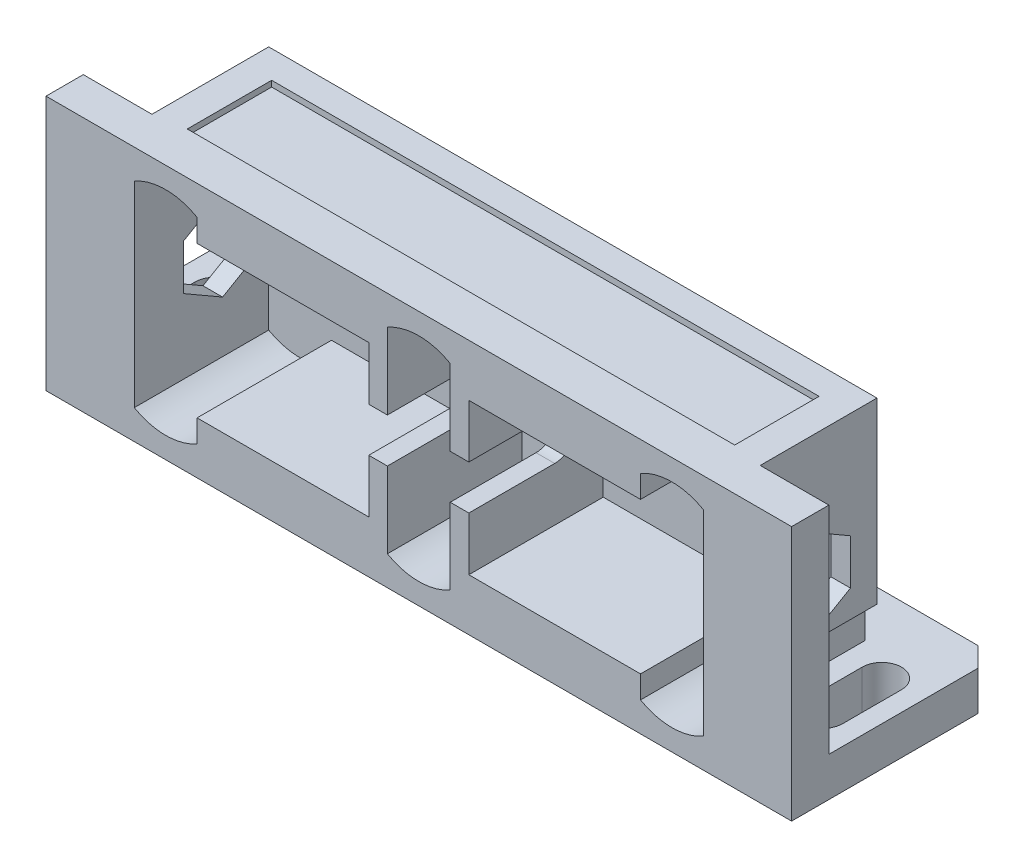
SolidWorks part; units mm, degrees
ref_plane "Front Plane" through (0, 0, 0) normal (0, 0, 1) x (1, 0, 0)
ref_plane "Top Plane" through (0, 0, 0) normal (0, 1, 0) x (1, 0, 0)
ref_plane "Right Plane" through (0, 0, 0) normal (1, 0, 0) x (0, 0, -1)
sketch "Sketch1" plane through (0, 0, 0) normal (0, 1, 0) x (1, 0, 0)
  line L1 (38, 10.5) -> (-38, 10.5)
  line L2 (38, 10.5) -> (38, -10.5)
  line L3 (38, -10.5) -> (-38, -10.5)
  line L4 (-38, 10.5) -> (-38, -10.5)
  line L5 (38, 10.5) -> (-38, -10.5) construction
  line L6 (38, -10.5) -> (-38, 10.5) construction
  point P0 (0, 0)
  dimension "D1" = 76
  dimension "D2" = 21
extrude "Boss-Extrude1" add sketch "Sketch1" along normal blind 4
sketch "Sketch2" plane through (0, 0, 0) normal (0, 1, 0) x (1, 0, 0)
  line L0 (-38, 10.5) -> (-38, -10.5) construction
  line L1 (-38, -6.7) -> (38, -6.7)
  line L2 (-38, -6.7) -> (-38, -10.5)
  line L3 (-38, -10.5) -> (38, -10.5)
  line L4 (38, -6.7) -> (38, -10.5)
  dimension "D1" = 3.8
extrude "Boss-Extrude2" add sketch "Sketch2" along normal blind 26
sketch "Sketch3" plane through (0, 0, 10.5) normal (0, 0, -1) x (-1, 0, 0)
  line L0 (-38, 26) -> (38, 26) construction
  line L1 (-31, 26) -> (31, 26)
  line L2 (-31, 26) -> (-31, 4)
  line L3 (-31, 4) -> (31, 4)
  line L4 (31, 26) -> (31, 4)
  line L5 (-38, 4) -> (38, 4) construction
  line L6 (0, 4) -> (0, 0) construction
  line L7 (-38, 0) -> (38, 0) construction
  dimension "D1" = 62
extrude "Boss-Extrude3" add sketch "Sketch3" along normal blind 15.7
chamfer "Chamfer2" distance 2 angle 45 2 edges at (-38, 2, -10.5) (38, 2, -10.5)
sketch "Sketch4" plane through (0, 26, 0) normal (0, 1, 0) x (1, 0, 0)
  line L3 (31, 5.2) -> (-31, 5.2) construction
  line L4 (-27.9, 2.4) -> (27.9, 2.4)
  line L5 (-27.9, 2.4) -> (-27.9, -6.2)
  line L6 (-27.9, -6.2) -> (27.9, -6.2)
  line L7 (27.9, 2.4) -> (27.9, -6.2)
  line L8 (31, 5.2) -> (31, -6.7) construction
  line L9 (0, 0) -> (0, -6.2) construction
  line L10 (-38, -10.5) -> (38, -10.5) construction
  dimension "D1" = 2.8
  dimension "D2" = 3.1
  dimension "D3" = 4.3
extrude "Cut-Extrude1" cut sketch "Sketch4" against normal blind 0.6
sketch "Sketch5" plane through (0, 4, 0) normal (0, 1, 0) x (1, 0, 0)
  line L0 (-34, 2.7) -> (-34, -3.3) construction
  line L1 (-32, 2.7) -> (-32, -3.3)
  line L2 (-36, 2.7) -> (-36, -3.3)
  line L3 (0, 0) -> (0, 10.5) construction
  line L4 (36, 10.5) -> (-36, 10.5) construction
  line L5 (34, 2.7) -> (34, -3.3) construction
  line L6 (32, 2.7) -> (32, -3.3)
  line L7 (36, 2.7) -> (36, -3.3)
  line L8 (-38, 8.5) -> (-38, -6.7) construction
  arc A0 (-32, 2.7) -> (-36, 2.7) centre (-34, 2.7) ccw
  arc A1 (-36, -3.3) -> (-32, -3.3) centre (-34, -3.3) ccw
  arc A2 (32, 2.7) -> (36, 2.7) centre (34, 2.7) cw
  arc A3 (36, -3.3) -> (32, -3.3) centre (34, -3.3) cw
  point P2 (-34, -0.3)
  point P14 (34, -0.3)
  point P19 (-34, 4.7)
  dimension "D1" = 4
  dimension "D2" = 8
  dimension "D3" = 5.8
  dimension "D4" = 2
extrude "Cut-Extrude2" cut sketch "Sketch5" against normal through all
sketch "Sketch6" plane through (0, 0, -10.5) normal (0, 0, -1) x (-1, 0, 0)
  line L0 (0, 0) -> (0, 26) construction
  line L1 (-16.75, 1.1) -> (-8.75, 1.1)
  line L2 (-16.75, 1.1) -> (-16.75, 5.1)
  line L3 (-16.75, 5.1) -> (-8.75, 5.1)
  line L4 (-8.75, 1.1) -> (-8.75, 5.1)
  line L5 (31, 26) -> (-31, 26) construction
  line L6 (8.75, 1.1) -> (8.75, 5.1)
  line L7 (16.75, 5.1) -> (8.75, 5.1)
  line L8 (16.75, 1.1) -> (16.75, 5.1)
  line L9 (16.75, 1.1) -> (8.75, 1.1)
  line L10 (-36, 0) -> (36, 0) construction
  dimension "D1" = 8
  dimension "D2" = 4
  dimension "D3" = 1.1
  dimension "D4" = 17.5
extrude "Cut-Extrude3" cut sketch "Sketch6" against normal blind 19.7
sketch "Sketch7" plane through (0, 0, 10.5) normal (0, 0, 1) x (1, 0, 0)
  line L0 (-38, 13) -> (0, 13) construction
  line L1 (29, 5.3) -> (-29, 5.3)
  line L2 (29, 5.3) -> (29, 20.7)
  line L3 (29, 20.7) -> (-29, 20.7)
  line L4 (-29, 5.3) -> (-29, 20.7)
  line L5 (29, 5.3) -> (-29, 20.7) construction
  line L6 (29, 20.7) -> (-29, 5.3) construction
  line L7 (-38, 26) -> (-38, 0) construction
  point P0 (0, 13)
  dimension "D1" = 58
  dimension "D2" = 15.4
extrude "Cut-Extrude4" cut sketch "Sketch7" against normal blind 13.7
sketch "Sketch8" plane through (0, 0, 10.5) normal (0, 0, 1) x (1, 0, 0)
  line L0 (-29, 20.7) -> (-29, 5.3) construction
  line L9 (-29, 20.7) -> (-29, 5.3) construction
  line L10 (-29, 23) -> (-22.6, 23) construction
  line L11 (-38, 13) -> (-29, 13) construction
  line L12 (-29, 23) -> (-29, 3)
  line L13 (-29, 3) -> (-22.6, 3) construction
  line L14 (-22.6, 23) -> (-22.6, 3)
  line L16 (-38, 26) -> (-38, 0) construction
  arc A0 (-29, 23) -> (-22.6, 23) centre (-25.8, 17.4015) cw
  arc A1 (-29, 3) -> (-22.6, 3) centre (-25.8, 8.5985) ccw
  point P9 (-25.8, 23.85)
  point P11 (-25.8, 2.15)
  dimension "D2" = 21.7
  dimension "D1" = 6.4
  dimension "D3" = 20
extrude "Cut-Extrude5" cut sketch "Sketch8" against normal up to surface (13.7 mm away) up to face at (0, 13, -3.2)
pattern_linear "LPattern1" count 3 spacing 25.8 along (1, 0, 0) of "Cut-Extrude5"
sketch "Sketch9" plane through (0, 0, 10.5) normal (0, 0, 1) x (1, 0, 0)
  line L0 (-22.6, 5.3) -> (-3.2, 5.3) construction
  line L6 (-3.2, 20.7) -> (-5.1, 20.7)
  line L20 (-3.2, 20.7) -> (-3.2, 5.3)
  line L21 (-3.2, 5.3) -> (-5.1, 5.3)
  line L22 (-5.1, 20.7) -> (-5.1, 5.3)
  line L23 (0, 0) -> (0, 26) construction
  line L24 (-38, 26) -> (38, 26) construction
  line L25 (5.1, 20.7) -> (5.1, 5.3)
  line L26 (3.2, 5.3) -> (5.1, 5.3)
  line L27 (3.2, 20.7) -> (3.2, 5.3)
  line L28 (3.2, 20.7) -> (5.1, 20.7)
  dimension "D1" = 1.9
extrude "Boss-Extrude4" add sketch "Sketch9" against normal up to next
sketch "Sketch10" plane through (-5.1, 0, 0) normal (-1, 0, 0) x (0, 0, 1)
  line L0 (10.5, 20.7) -> (10.5, 5.3) construction
  line L1 (10.5, 15.25) -> (1.75, 15.25)
  line L2 (10.5, 15.25) -> (10.5, 10.75)
  line L3 (10.5, 10.75) -> (1.75, 10.75)
  line L4 (1.75, 15.25) -> (1.75, 10.75) construction
  line L5 (-3.2, 13) -> (1.75, 13) construction
  line L6 (-3.2, 5.3) -> (-3.2, 20.7) construction
  arc A0 (1.75, 15.25) -> (1.75, 10.75) centre (1.75, 13) ccw
  point P11 (-0.5, 13)
  dimension "D1" = 4.5
  dimension "D2" = 11
extrude "Cut-Extrude6" cut sketch "Sketch10" against normal up to surface (10.2 mm away) up to face at (5.1, 13, 3.65)
sketch "Sketch11" plane through (-31, 0, 0) normal (-1, 0, 0) x (0, 0, 1)
  line L0 (1.5, 12.8812) -> (1.5, 17.5) construction
  line L1 (1.5, 17.5) -> (-2.5, 15.1906)
  line L2 (-2.5, 15.1906) -> (-2.5, 10.5718)
  line L3 (-2.5, 10.5718) -> (1.5, 8.2624)
  line L4 (1.5, 8.2624) -> (5.5, 10.5718)
  line L5 (5.5, 10.5718) -> (5.5, 15.1906)
  line L6 (5.5, 15.1906) -> (1.5, 17.5)
  line L7 (-5.2, 26) -> (6.7, 26) construction
  line L8 (-5.2, 4) -> (-5.2, 26) construction
  circle A0 centre (1.5, 12.8812) radius 4 construction
  dimension "D1" = 8
  dimension "D2" = 9.2376
  dimension "D3" = 8.5
  dimension "D4" = 2.7
extrude "Cut-Extrude7" cut sketch "Sketch11" against normal up to next
mirror "Mirror1" about plane through (0, 0, 0) normal (1, 0, 0) of "Cut-Extrude7"
sketch "Sketch12" plane through (0, 0, -5.2) normal (0, 0, -1) x (-1, 0, 0)
  line L0 (0, 0) -> (0, 26) construction
  line L1 (-31, 4) -> (-29.8, 4)
  line L2 (-31, 4) -> (-31, 7.8)
  line L3 (-31, 7.8) -> (-29.8, 7.8)
  line L4 (-29.8, 4) -> (-29.8, 7.8)
  line L5 (31, 26) -> (-31, 26) construction
  line L6 (29.8, 4) -> (29.8, 7.8)
  line L7 (31, 7.8) -> (29.8, 7.8)
  line L8 (31, 4) -> (31, 7.8)
  line L9 (31, 4) -> (29.8, 4)
  dimension "D1" = 3.8
  dimension "D2" = 1.2
extrude "Cut-Extrude8" cut sketch "Sketch12" against normal up to surface (11.9 mm away) up to face at (34.5, 15, 6.7)
